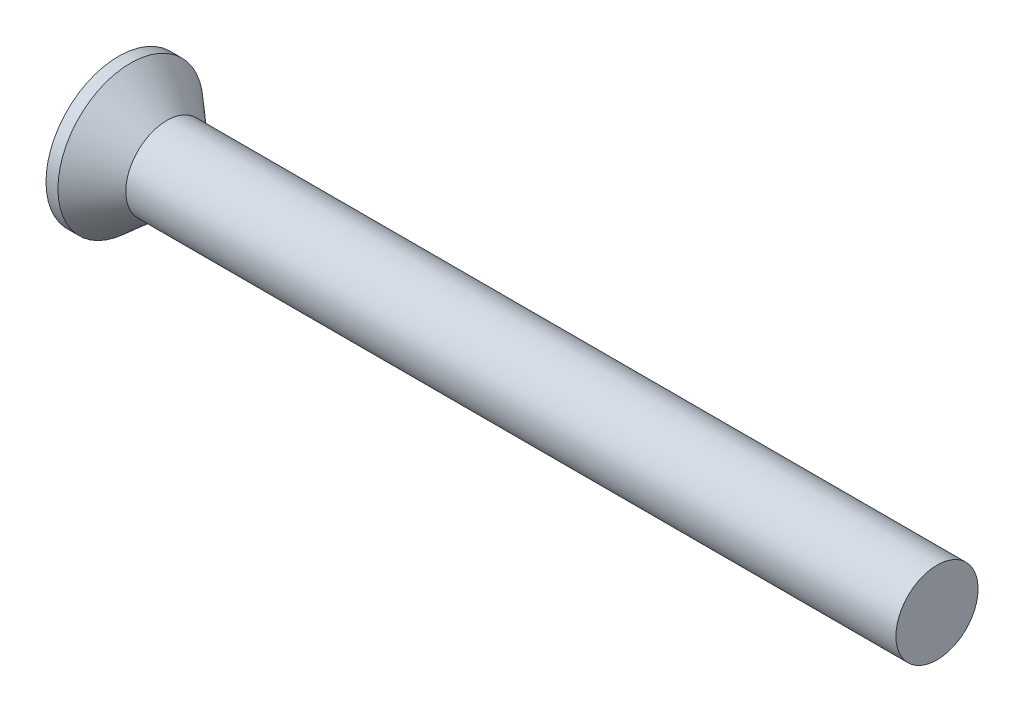
SolidWorks part; units mm, degrees
revolve "Base-Revolve" add sketch "BodySke" angle 360 about L5
sketch "BodySke" plane through (0, 0, 0) normal (0, 0, 1) x (1, 0, 0)
  line L0 (0, 0) -> (0, 3.0988)
  line L1 (0, 3.0988) -> (0.5088, 3.0988)
  line L2 (2.0574, 1.7526) -> (34.925, 1.7526)
  line L3 (34.925, 1.7526) -> (34.925, 0)
  line L4 (34.925, 0) -> (0, 0)
  line L5 (-6.35, 0) -> (82.55, 0) construction
  line L6 (2.0574, -1.7526) -> (34.925, -1.7526) construction
  line L7 (0.5088, -3.0988) -> (2.0574, -1.7526) construction
  line L8 (0.5088, 3.0988) -> (2.0574, 1.7526)
  line L9 (0, -3.0988) -> (0.5088, -3.0988) construction
  line L10 (2.6924, 3.3401) -> (2.6924, -6.1849) construction
  line L11 (9.525, 6.35) -> (9.525, -3.175) construction
  dimension "Diameter" = 3.5052
  dimension "Length" = 34.925
  dimension "Head_ht" = 2.0574
  dimension "Head_dia" = 6.1976
  dimension "Head_ang" = 82
  dimension "D6" = 0.5088
  dimension "Advance" = 0.635
  dimension "Thread_nom" = 25.4
cosmetic thread "ThreadCosmetic" [suppressed] parameters "Thread_length"=25.4, "Thread_minor"=2.7483
extrude "Slot" [suppressed] cut sketch "Sketch2" against normal blind 0.9652
sketch "Sketch2" plane through (0, 0, 0) normal (-1, 0, 0) x (0, 0, 1)
  line L0 (-3.0988, -0.6096) -> (3.0988, -0.6096)
  line L1 (-3.0988, -0.6096) -> (-3.0988, 0.6096)
  line L2 (3.0988, 0.6096) -> (-3.0988, 0.6096)
  line L3 (3.0988, 0.6096) -> (3.0988, -0.6096)
  dimension "Slot_width" = 1.2192
  dimension "D1" = 0.6096
  dimension "D2" = 6.1976
  dimension "D3" = 3.0988
ref_plane "Plane1" through (0, 0, 0) normal (0, 0, 1) x (1, 0, 0)
ref_plane "Plane2" through (0, 0, 0) normal (0, 1, 0) x (1, 0, 0)
ref_plane "Plane3" through (0, 0, 0) normal (1, 0, 0) x (0, 0, -1)
sketch "Sketch3" plane through (0, 0, 0) normal (-1, 0, 0) x (0, 0, 1)
  line L0 (-0.4826, 2.4765) -> (0.4826, 2.4765)
  line L1 (0.4826, 2.4765) -> (0.4826, -2.4765)
  line L2 (0.4826, -2.4765) -> (-0.4826, -2.4765)
  line L3 (-0.4826, -2.4765) -> (-0.4826, 2.4765)
  dimension "Cross_dia" = 4.953
  dimension "Cross_width" = 0.9652
  dimension "D1" = 2.4765
  dimension "D2" = 0.4826
ref_plane "Plane4" through (2.8702, 0, 0) normal (-1, 0, 0) x (0, 0, 1)
sketch "Sketch4" plane through (2.8702, 0, 0) normal (-1, 0, 0) x (0, 0, 1)
  line L0 (-0.2413, 0.2413) -> (0.2413, 0.2413)
  line L3 (0.2413, 0.2413) -> (0.2413, -0.2413)
  line L4 (0.2413, -0.2413) -> (-0.2413, -0.2413)
  line L5 (-0.2413, -0.2413) -> (-0.2413, 0.2413)
  dimension "D2" = 0.4826
  dimension "D1" = 0.4826
  dimension "D3" = 0.2413
  dimension "D4" = 0.2413
loft "Cross" cut profiles "Sketch3", "Sketch4"
pattern_circular "CirPattern1" count 2 every 90 about axis through (0, 0, 0) along (1, 0, 0) of "Cross"
sketch "ThdSchSke" plane through (0, 0, 0) normal (0, 0, 1) x (1, 0, 0)
  line L0 (9.525, -1.3741) -> (9.26, -1.7526)
  line L1 (9.525, -1.3741) -> (9.79, -1.7526)
  line L2 (9.79, -1.7526) -> (9.79, -2.1907)
  line L3 (-3.175, 0) -> (5.1513, 0) construction
  line L5 (9.79, -2.1907) -> (9.26, -2.1907)
  line L6 (9.26, -2.1907) -> (9.26, -1.7526)
  line L7 (0, 3.0988) -> (0, -3.0988) construction
  dimension "Diameter" = 3.5052
  dimension "Thread_minor" = 2.7483
  dimension "Start" = 9.525
revolve "ThreadSchematic" [suppressed] cut sketch "ThdSchSke" angle 360 about L3
pattern_linear "ThdSchPat" [suppressed]
equation "\"D1@Sketch3\" = \"Cross_dia@Sketch3\" / 2"
equation "\"D2@Sketch3\" = \"Cross_width@Sketch3\" / 2"
equation "\"D1@Sketch4\" = \"Cross_width@Sketch3\" *.5"
equation "\"D2@Sketch4\" = \"D1@Sketch4\""
equation "\"D4@Sketch4\" = \"D2@Sketch4\" / 2"
equation "\"D3@Sketch4\" = \"D1@Sketch4\" / 2"
equation "\"D1@Sketch2\" = \"Slot_width@Sketch2\" / 2"
equation "\"D2@Sketch2\" = \"Head_dia@BodySke\""
equation "\"D3@Sketch2\" = \"D2@Sketch2\" / 2"
equation "\"Thread_length@ThreadCosmetic\" = ((sgn( (\"Length@BodySke\" - \"Advance@BodySke\" - \"Head_ht@BodySke\" ) - \"Thread_nom@BodySke\" )-1)*( (\"Length@BodySke\" - \"Advance@BodySke\" - \"Head_ht@BodySke\" ) - \"Thread_nom@BodySke\" ))/-2+ \"Thread_nom@BodySke\""
equation "\"Thread_minor@ThdSchSke\" = \"Thread_minor@ThreadCosmetic\""
equation "\"Diameter@ThdSchSke\" = \"Diameter@BodySke\""
equation "\"Overcut@ThdSchSke\" = \"Diameter@BodySke\" * 1.25"
equation "\"Start@ThdSchSke\" = 0.000001 + \"Length@BodySke\" - \"Thread_length@ThreadCosmetic\"  '---Countersunk---"
equation "\"Num_threads@ThdSchPat\" = int( \"Thread_length@ThreadCosmetic\" / \"Advance@BodySke\" + 0.999 )  + 1"
equation "\"Advance@ThdSchPat\" = \"Thread_length@ThreadCosmetic\" /  (\"Num_threads@ThdSchPat\" - 1) 'relax it"
